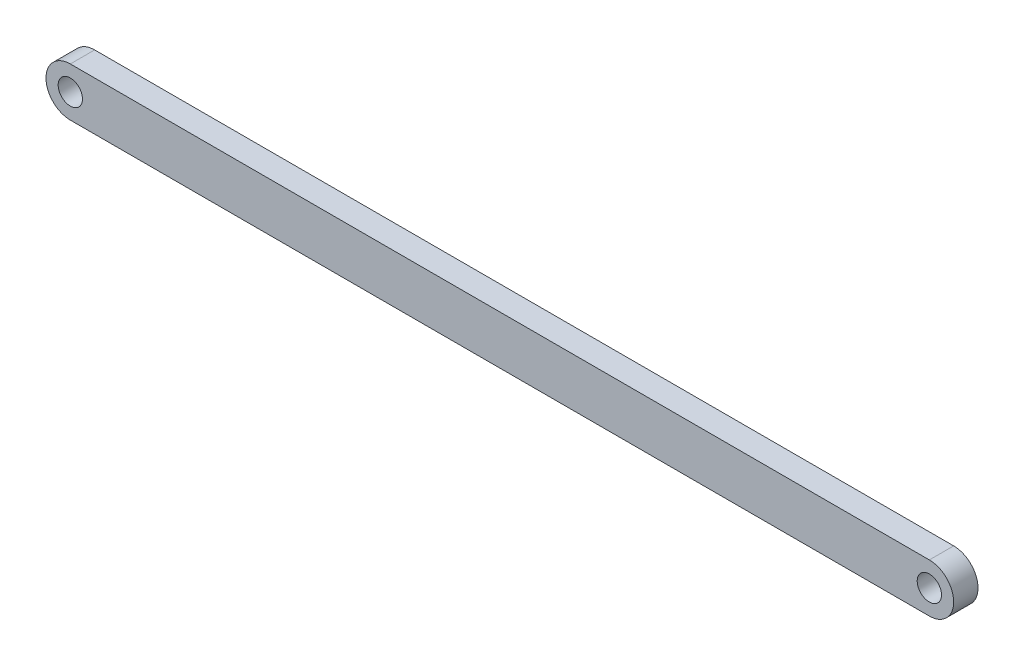
SolidWorks part; units mm, degrees
ref_plane "Front Plane" through (0, 0, 0) normal (0, 0, 1) x (1, 0, 0)
ref_plane "Top Plane" through (0, 0, 0) normal (0, 1, 0) x (1, 0, 0)
ref_plane "Right Plane" through (0, 0, 0) normal (1, 0, 0) x (0, 0, -1)
sketch "Sketch1" plane through (0, 0, 0) normal (0, 0, 1) x (1, 0, 0)
  line L0 (-112.141, 0) -> (112.141, 0) construction
  line L1 (-112.141, 6.35) -> (112.141, 6.35)
  line L2 (-112.141, -6.35) -> (112.141, -6.35)
  arc A0 (-112.141, 6.35) -> (-112.141, -6.35) centre (-112.141, 0) ccw
  arc A1 (112.141, -6.35) -> (112.141, 6.35) centre (112.141, 0) ccw
  circle A2 centre (-112.141, 0) radius 3.175
  circle A3 centre (112.141, 0) radius 3.175
  point P2 (0, 0)
  dimension "D1" = 6.35
  dimension "D2" = 6.35
  dimension "D3" = 12.7
  dimension "D4" = 224.282
extrude "Boss-Extrude1" add sketch "Sketch1" along normal blind 6.35
equation "\"q\"=0.25"
